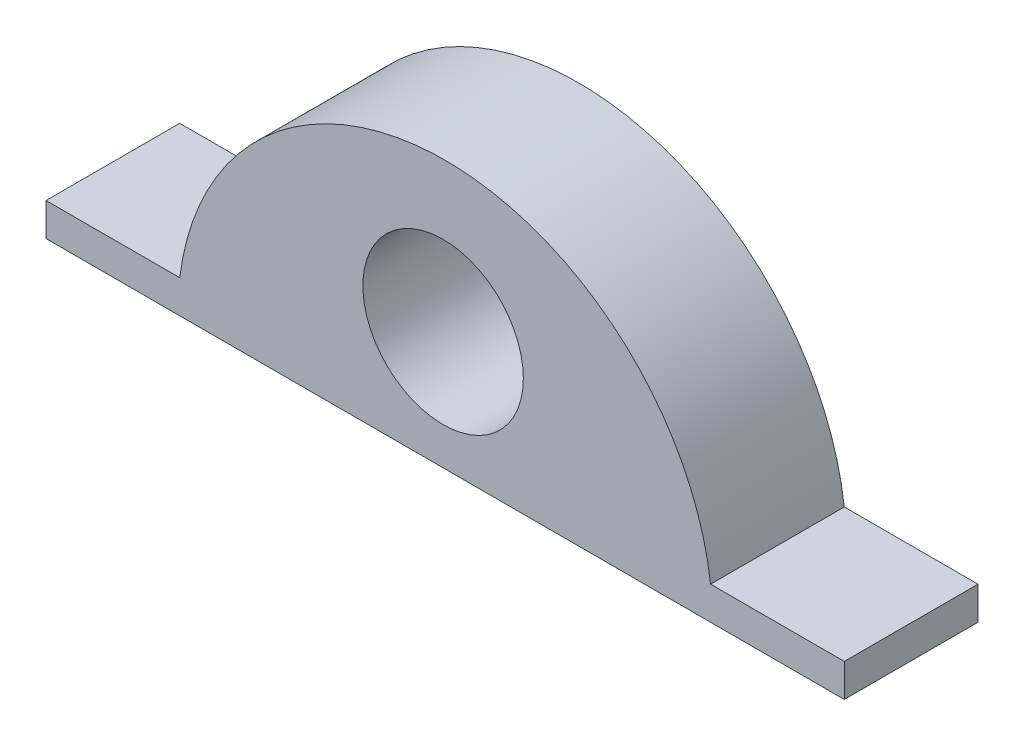
SolidWorks part; units mm, degrees
ref_plane "Front Plane" through (0, 0, 0) normal (0, 0, 1) x (1, 0, 0)
ref_plane "Top Plane" through (0, 0, 0) normal (0, 1, 0) x (1, 0, 0)
ref_plane "Right Plane" through (0, 0, 0) normal (1, 0, 0) x (0, 0, -1)
sketch "Sketch1" plane through (0, 0, 0) normal (0, 0, 1) x (1, 0, 0)
  line L3 (-49.6163, -44.2946) -> (49.6206, -44.2946)
  line L4 (49.6206, -38.1295) -> (74.6206, -38.1295)
  line L6 (49.6206, -44.2946) -> (74.6206, -44.2946)
  line L7 (74.6206, -38.1295) -> (74.6206, -44.2946)
  line L8 (-49.6163, -38.1295) -> (-74.6163, -38.1295)
  line L10 (-49.6163, -44.2946) -> (-74.6163, -44.2946)
  line L11 (-74.6163, -38.1295) -> (-74.6163, -44.2946)
  arc A0 (-49.6163, -38.1295) -> (49.6206, -38.1295) centre (0.0021, -44.2946) cw
  circle A1 centre (-0.3794, -22.2946) radius 15
  point P0 (0, 0)
  dimension "D1" = 75
  dimension "D2" = 25
  dimension "D3" = 25
  dimension "D4" = 6.1651
  dimension "D5" = 22
extrude "Boss-Extrude1" add sketch "Sketch1" along normal blind 25
